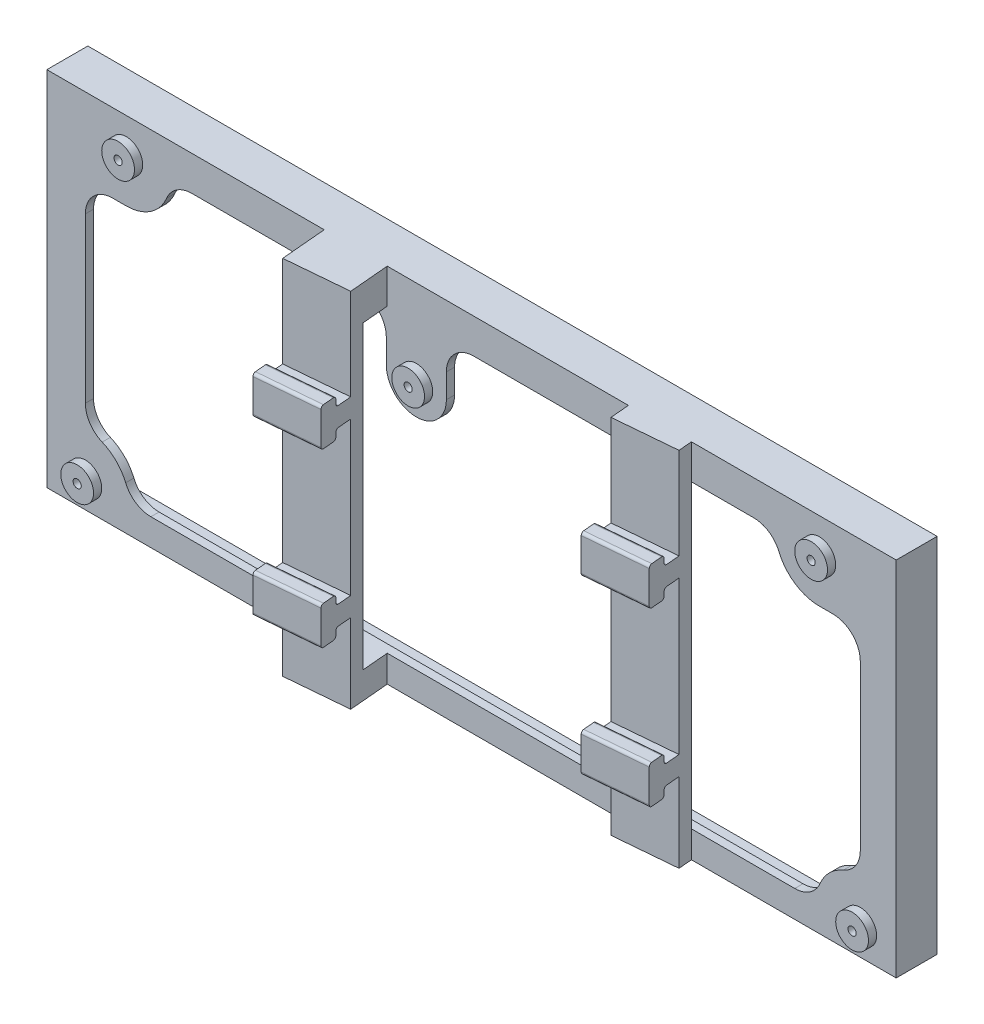
SolidWorks part; units mm, degrees
ref_plane "Front Plane" through (0, 0, 0) normal (0, 0, 1) x (1, 0, 0)
ref_plane "Top Plane" through (0, 0, 0) normal (0, 1, 0) x (1, 0, 0)
ref_plane "Right Plane" through (0, 0, 0) normal (1, 0, 0) x (0, 0, -1)
sketch "Sketch1" plane through (0, 0, 0) normal (0, 0, 1) x (1, 0, 0)
  circle A0 centre (0, 0) radius 1.5
  circle A1 centre (-106.24, 18.83) radius 1.5
  circle A2 centre (147.61, 18.83) radius 1.5
  circle A3 centre (-121.24, -91.25) radius 1.5
  circle A4 centre (162.61, -91.25) radius 1.5
  circle A5 centre (0, 0) radius 6
  circle A6 centre (-106.24, 18.83) radius 6
  circle A7 centre (147.61, 18.83) radius 6
  circle A8 centre (-121.24, -91.25) radius 6
  circle A9 centre (162.61, -91.25) radius 6
  dimension "D1" = 3
  dimension "D4" = 18.83
  dimension "D5" = 162.61
  dimension "D2" = 147.61
  dimension "D3" = 106.24
  dimension "D6" = 121.24
  dimension "D7" = 91.25
  dimension "D8" = 4.5
extrude "Display screw pattern" add sketch "Sketch1" along normal blind 3
sketch "Sketch2" plane through (0, 0, 0) normal (0, 0, -1) x (-1, 0, 0)
  line L0 (135.34, 31.53) -> (135.34, -101.07)
  line L1 (133.84, 30.03) -> (-174.26, 30.03) construction
  line L2 (133.84, 30.03) -> (133.84, -99.57) construction
  line L3 (133.84, -99.57) -> (-174.26, -99.57) construction
  line L4 (-174.26, 30.03) -> (-174.26, -99.57) construction
  line L5 (135.34, -101.07) -> (-175.76, -101.07)
  line L6 (-175.76, 31.53) -> (-175.76, -101.07)
  line L7 (135.34, 31.53) -> (-175.76, 31.53)
  circle A2 centre (106.24, 18.83) radius 4
  circle A3 centre (106.24, 18.83) radius 4
  circle A8 centre (0, 0) radius 4
  circle A9 centre (0, 0) radius 4
  circle A11 centre (121.24, -91.25) radius 4
  circle A12 centre (121.24, -91.25) radius 4
  circle A14 centre (-147.61, 18.83) radius 4
  circle A15 centre (-147.61, 18.83) radius 4
  circle A17 centre (-162.61, -91.25) radius 4
  circle A18 centre (-162.61, -91.25) radius 4
  dimension "D6" = 11.2
  dimension "D7" = 26.65
  dimension "D8" = 8.32
  dimension "D9" = 27.6
  dimension "D1" = 2
  dimension "D2" = 2
  dimension "D3" = 2
  dimension "D4" = 2
  dimension "D5" = 2
  dimension "D10" = 1.5
extrude "Display backplane" add sketch "Sketch2" along normal blind 3
sketch "Sketch3" plane through (0, 0, 0) normal (0, 0, 1) x (1, 0, 0)
  line L1 (162.61, -7.17) -> (162.61, -67.25)
  line L2 (138.61, -91.25) -> (-97.24, -91.25)
  line L3 (-121.24, -67.25) -> (-121.24, -7.17)
  line L5 (-82.24, 18.83) -> (-21, 18.83)
  line L6 (11, 8.83) -> (11, 0)
  line L7 (-11, 0) -> (-11, 8.83)
  line L8 (21, 18.83) -> (123.61, 18.83)
  line L9 (147.61, 2.83) -> (152.61, 2.83)
  line L10 (-106.24, 2.83) -> (-111.24, 2.83)
  arc A0 (123.61, 18.83) -> (132.8408, 12.6762) centre (123.61, 8.83) cw
  arc A1 (152.61, 2.83) -> (162.61, -7.17) centre (152.61, -7.17) cw
  arc A2 (162.61, -67.25) -> (156.4562, -76.4808) centre (152.61, -67.25) cw
  circle A4 centre (-121.24, -91.25) radius 16
  arc A5 (-106.4708, -85.0962) -> (-115.0862, -76.4808) centre (-121.24, -91.25) ccw
  arc A6 (138.61, -91.25) -> (147.8408, -85.0962) centre (138.61, -81.25) ccw
  circle A7 centre (162.61, -91.25) radius 16
  arc A8 (156.4562, -76.4808) -> (147.8408, -85.0962) centre (162.61, -91.25) ccw
  arc A9 (-97.24, -91.25) -> (-106.4708, -85.0962) centre (-97.24, -81.25) cw
  arc A10 (-121.24, -67.25) -> (-115.0862, -76.4808) centre (-111.24, -67.25) ccw
  arc A11 (-111.24, 2.83) -> (-121.24, -7.17) centre (-111.24, -7.17) ccw
  arc A12 (-82.24, 18.83) -> (-91.4708, 12.6762) centre (-82.24, 8.83) ccw
  circle A15 centre (0, 0) radius 11
  arc A16 (-11, 0) -> (11, 0) centre (0, 0) ccw
  arc A29 (21, 18.83) -> (11, 8.83) centre (21, 8.83) ccw
  arc A30 (-11, 8.83) -> (-21, 18.83) centre (-21, 8.83) ccw
  circle A36 centre (-106.24, 18.83) radius 16
  arc A37 (-106.24, 2.83) -> (-91.4708, 12.6762) centre (-106.24, 18.83) ccw
  circle A38 centre (147.61, 18.83) radius 16
  arc A39 (132.8408, 12.6762) -> (147.61, 2.83) centre (147.61, 18.83) ccw
  point P29 (131.61, 18.83)
  point P43 (162.61, -75.25)
  point P47 (146.61, -91.25)
  point P50 (-105.24, -91.25)
  point P53 (-121.24, -75.25)
  point P58 (-90.24, 18.83)
  dimension "D6" = 10
  dimension "D7" = 10
  dimension "D1" = 10
  dimension "D2" = 5
  dimension "D3" = 10
  dimension "D4" = 10
  dimension "D5" = 10
extrude "Backplane weight reduction" cut sketch "Sketch3" against normal through all both and the other way through all
sketch "Sketch4" plane through (0, 0, -3) normal (0, 0, -1) x (-1, 0, 0)
  line L12 (134.34, 30.53) -> (-174.76, 30.53)
  line L13 (-174.76, 30.53) -> (-174.76, -100.07)
  line L14 (-174.76, -100.07) -> (134.34, -100.07)
  line L15 (134.34, -100.07) -> (134.34, 30.53)
  line L16 (135.34, 31.53) -> (-175.76, 31.53)
  line L17 (-175.76, 31.53) -> (-175.76, -101.07)
  line L18 (-175.76, -101.07) -> (135.34, -101.07)
  line L19 (135.34, -101.07) -> (135.34, 31.53)
  line L20 (135.34, 31.53) -> (-175.76, 31.53)
  line L21 (-175.76, 31.53) -> (-175.76, -101.07)
  line L22 (-175.76, -101.07) -> (135.34, -101.07)
  line L23 (135.34, -101.07) -> (135.34, 31.53)
  dimension "D1" = 0
  dimension "D2" = 1
extrude "Display outside craddle" add sketch "Sketch4" along normal blind 12
sketch "Mount point plane pivot sketch" plane through (0, 0, 0) normal (0, 0, 1) x (1, 0, 0)
  line L0 (100.76, 31.53) -> (100.76, -101.07)
  line L1 (-135.34, 31.53) -> (175.76, 31.53) construction
  line L2 (175.76, -101.07) -> (-135.34, -101.07) construction
  line L3 (175.76, 31.53) -> (175.76, -101.07) construction
  dimension "D1" = 75
ref_plane "Mount point plane" through (0.7654, 0, 8.7484) normal (0.0872, 0, 0.9962) x (0, -1, 0)
sketch "Sketch7" plane through (0.7654, 0, 8.7484) normal (0.0872, 0, 0.9962) x (0, -1, 0)
  line L0 (101.07, 175.0912) -> (101.07, -134.825) construction
  line L1 (-31.53, 100.3766) -> (101.07, 100.3766)
  line L2 (-31.53, 100.3766) -> (-31.53, 77.3766)
  line L3 (-31.53, 77.3766) -> (101.07, 77.3766)
  line L4 (101.07, 100.3766) -> (101.07, 77.3766)
  line L5 (-31.53, -134.825) -> (-31.53, 175.0912) construction
  line L6 (-31.53, -10.6234) -> (101.07, -10.6234)
  line L7 (-31.53, -10.6234) -> (-31.53, -33.6234)
  line L8 (-31.53, -33.6234) -> (101.07, -33.6234)
  line L9 (101.07, -10.6234) -> (101.07, -33.6234)
  dimension "D1" = 111
  dimension "D2" = 23
extrude "Slot interface backing block" add sketch "Sketch7" along normal blind 5 separate body
sketch "Sketch8" plane through (0.7654, 0, 8.7484) normal (-0.0872, 0, -0.9962) x (-0.9962, 0, 0.0872)
  line L0 (-77.3766, 31.53) -> (-100.3766, 31.53) construction
  line L1 (-100.3766, 31.53) -> (-100.3766, -101.07) construction
  line L2 (-100.3766, -101.07) -> (-77.3766, -101.07) construction
  line L3 (-77.3766, -101.07) -> (-77.3766, 31.53) construction
  line L4 (33.6234, 31.53) -> (10.6234, 31.53) construction
  line L5 (10.6234, 31.53) -> (10.6234, -101.07) construction
  line L6 (10.6234, -101.07) -> (33.6234, -101.07) construction
  line L7 (33.6234, -101.07) -> (33.6234, 31.53) construction
  line L8 (-77.3766, 31.53) -> (-100.3766, 31.53)
  line L9 (-100.3766, 31.53) -> (-100.3766, 18.83)
  line L10 (-100.3766, -101.07) -> (-77.3766, -101.07)
  line L11 (-77.3766, -101.07) -> (-77.3766, -91.25)
  line L12 (33.6234, 31.53) -> (10.6234, 31.53)
  line L13 (10.6234, 31.53) -> (10.6234, 18.83)
  line L14 (10.6234, -101.07) -> (33.6234, -101.07)
  line L15 (33.6234, -101.07) -> (33.6234, -91.25)
  line L16 (-100.3766, 18.83) -> (-77.3766, 18.83)
  line L17 (-123.4011, 18.83) -> (-21.1816, 18.83) construction
  line L18 (33.6234, 18.83) -> (10.6234, 18.83)
  line L19 (20.6586, 18.83) -> (81.6656, 18.83) construction
  line L20 (10.6234, -91.25) -> (33.6234, -91.25)
  line L21 (96.6085, -91.25) -> (-138.344, -91.25) construction
  line L22 (-100.3766, -91.25) -> (-77.3766, -91.25)
  line L23 (-100.3766, -91.25) -> (-100.3766, -101.07)
  line L24 (-77.3766, 18.83) -> (-77.3766, 31.53)
  line L25 (10.6234, -91.25) -> (10.6234, -101.07)
  line L26 (33.6234, 18.83) -> (33.6234, 31.53)
extrude "Slot backing connection" add sketch "Sketch8" along normal up to next
sketch "Sketch9" plane through (-33.4955, 0, 2.9305) normal (-0.9962, 0, 0.0872) x (0.0872, 0, 0.9962)
  line L0 (13.7818, -1.97) -> (18.7818, -1.97)
  line L1 (13.7818, 31.53) -> (13.7818, -101.07) construction
  line L2 (19.7818, -0.97) -> (19.7818, 0.53)
  line L3 (20.7818, 1.53) -> (24.7818, 1.53)
  line L4 (25.7818, 0.53) -> (25.7818, -11.47)
  line L5 (24.7818, -12.47) -> (20.7818, -12.47)
  line L6 (19.7818, -11.47) -> (19.7818, -9.97)
  line L7 (18.7818, -8.97) -> (13.7818, -8.97)
  line L8 (13.7818, -8.97) -> (13.7818, -1.97)
  line L17 (13.7818, -71.97) -> (13.7818, -64.97)
  line L18 (13.7818, -64.97) -> (18.7818, -64.97)
  line L19 (19.7818, -63.97) -> (19.7818, -62.47)
  line L20 (20.7818, -61.47) -> (24.7818, -61.47)
  line L21 (25.7818, -62.47) -> (25.7818, -74.47)
  line L22 (24.7818, -75.47) -> (20.7818, -75.47)
  line L23 (19.7818, -74.47) -> (19.7818, -72.97)
  line L24 (18.7818, -71.97) -> (13.7818, -71.97)
  arc A0 (18.7818, -1.97) -> (19.7818, -0.97) centre (18.7818, -0.97) ccw
  arc A1 (19.7818, -9.97) -> (18.7818, -8.97) centre (18.7818, -9.97) ccw
  arc A2 (20.7818, -12.47) -> (19.7818, -11.47) centre (20.7818, -11.47) cw
  arc A3 (25.7818, -11.47) -> (24.7818, -12.47) centre (24.7818, -11.47) cw
  arc A4 (24.7818, 1.53) -> (25.7818, 0.53) centre (24.7818, 0.53) cw
  arc A5 (19.7818, 0.53) -> (20.7818, 1.53) centre (20.7818, 0.53) cw
  arc A6 (18.7818, -64.97) -> (19.7818, -63.97) centre (18.7818, -63.97) ccw
  arc A7 (19.7818, -62.47) -> (20.7818, -61.47) centre (20.7818, -62.47) cw
  arc A8 (24.7818, -61.47) -> (25.7818, -62.47) centre (24.7818, -62.47) cw
  arc A9 (25.7818, -74.47) -> (24.7818, -75.47) centre (24.7818, -74.47) cw
  arc A10 (20.7818, -75.47) -> (19.7818, -74.47) centre (20.7818, -74.47) cw
  arc A11 (19.7818, -72.97) -> (18.7818, -71.97) centre (18.7818, -72.97) ccw
  point P10 (13.7818, -5.47)
  point P11 (25.7818, -5.47)
  point P23 (19.7818, -1.97)
  point P30 (25.7818, -12.47)
  point P33 (25.7818, 1.53)
  point P36 (19.7818, 1.53)
  dimension "D8" = 1
  dimension "D1" = 14
  dimension "D2" = 6
  dimension "D3" = 6
  dimension "D4" = 7
  dimension "D6" = 63
  dimension "D7" = 30
  dimension "D5" = 2
extrude "Slots right (ignore SW axes in this part)" add sketch "Sketch9" against normal up to surface (23 mm away) up to face at (-10.1319, -35.49, 6.0824)
sketch "Sketch10" plane through (77.0821, 0, -6.7438) normal (-0.9962, 0, 0.0872) x (0.0872, 0, 0.9962)
  line L8 (19.7818, 0.53) -> (19.7818, -0.97)
  line L9 (18.7818, -1.97) -> (13.7818, -1.97)
  line L10 (13.7818, -1.97) -> (13.7818, -8.97)
  line L11 (13.7818, -8.97) -> (18.7818, -8.97)
  line L12 (19.7818, -9.97) -> (19.7818, -11.47)
  line L13 (20.7818, -12.47) -> (24.7818, -12.47)
  line L14 (25.7818, -11.47) -> (25.7818, 0.53)
  line L15 (24.7818, 1.53) -> (20.7818, 1.53)
  line L16 (19.7818, 0.53) -> (19.7818, -0.97)
  line L17 (18.7818, -1.97) -> (13.7818, -1.97)
  line L18 (13.7818, -1.97) -> (13.7818, -8.97)
  line L19 (13.7818, -8.97) -> (18.7818, -8.97)
  line L20 (19.7818, -9.97) -> (19.7818, -11.47)
  line L21 (20.7818, -12.47) -> (24.7818, -12.47)
  line L22 (25.7818, -11.47) -> (25.7818, 0.53)
  line L23 (24.7818, 1.53) -> (20.7818, 1.53)
  line L24 (19.7818, -62.47) -> (19.7818, -63.97)
  line L25 (18.7818, -64.97) -> (13.7818, -64.97)
  line L26 (13.7818, -64.97) -> (13.7818, -71.97)
  line L27 (13.7818, -71.97) -> (18.7818, -71.97)
  line L28 (19.7818, -72.97) -> (19.7818, -74.47)
  line L29 (20.7818, -75.47) -> (24.7818, -75.47)
  line L30 (25.7818, -74.47) -> (25.7818, -62.47)
  line L31 (24.7818, -61.47) -> (20.7818, -61.47)
  line L32 (19.7818, -62.47) -> (19.7818, -63.97)
  line L33 (18.7818, -64.97) -> (13.7818, -64.97)
  line L34 (13.7818, -64.97) -> (13.7818, -71.97)
  line L35 (13.7818, -71.97) -> (18.7818, -71.97)
  line L36 (19.7818, -72.97) -> (19.7818, -74.47)
  line L37 (20.7818, -75.47) -> (24.7818, -75.47)
  line L38 (25.7818, -74.47) -> (25.7818, -62.47)
  line L39 (24.7818, -61.47) -> (20.7818, -61.47)
  arc A6 (18.7818, -1.97) -> (19.7818, -0.97) centre (18.7818, -0.97) ccw
  arc A7 (19.7818, -9.97) -> (18.7818, -8.97) centre (18.7818, -9.97) ccw
  arc A8 (19.7818, -11.47) -> (20.7818, -12.47) centre (20.7818, -11.47) ccw
  arc A9 (24.7818, -12.47) -> (25.7818, -11.47) centre (24.7818, -11.47) ccw
  arc A10 (25.7818, 0.53) -> (24.7818, 1.53) centre (24.7818, 0.53) ccw
  arc A11 (20.7818, 1.53) -> (19.7818, 0.53) centre (20.7818, 0.53) ccw
  arc A12 (18.7818, -1.97) -> (19.7818, -0.97) centre (18.7818, -0.97) ccw
  arc A13 (19.7818, -9.97) -> (18.7818, -8.97) centre (18.7818, -9.97) ccw
  arc A14 (19.7818, -11.47) -> (20.7818, -12.47) centre (20.7818, -11.47) ccw
  arc A15 (24.7818, -12.47) -> (25.7818, -11.47) centre (24.7818, -11.47) ccw
  arc A16 (25.7818, 0.53) -> (24.7818, 1.53) centre (24.7818, 0.53) ccw
  arc A17 (20.7818, 1.53) -> (19.7818, 0.53) centre (20.7818, 0.53) ccw
  arc A18 (18.7818, -64.97) -> (19.7818, -63.97) centre (18.7818, -63.97) ccw
  arc A19 (19.7818, -72.97) -> (18.7818, -71.97) centre (18.7818, -72.97) ccw
  arc A20 (19.7818, -74.47) -> (20.7818, -75.47) centre (20.7818, -74.47) ccw
  arc A21 (24.7818, -75.47) -> (25.7818, -74.47) centre (24.7818, -74.47) ccw
  arc A22 (25.7818, -62.47) -> (24.7818, -61.47) centre (24.7818, -62.47) ccw
  arc A23 (20.7818, -61.47) -> (19.7818, -62.47) centre (20.7818, -62.47) ccw
  arc A24 (18.7818, -64.97) -> (19.7818, -63.97) centre (18.7818, -63.97) ccw
  arc A25 (19.7818, -72.97) -> (18.7818, -71.97) centre (18.7818, -72.97) ccw
  arc A26 (19.7818, -74.47) -> (20.7818, -75.47) centre (20.7818, -74.47) ccw
  arc A27 (24.7818, -75.47) -> (25.7818, -74.47) centre (24.7818, -74.47) ccw
  arc A28 (25.7818, -62.47) -> (24.7818, -61.47) centre (24.7818, -62.47) ccw
  arc A29 (20.7818, -61.47) -> (19.7818, -62.47) centre (20.7818, -62.47) ccw
  dimension "D1" = 0
  dimension "D2" = 0
extrude "Slots left" add sketch "Sketch10" against normal up to surface (23 mm away) up to face at (100.9053, -35.25, 1.6603)
